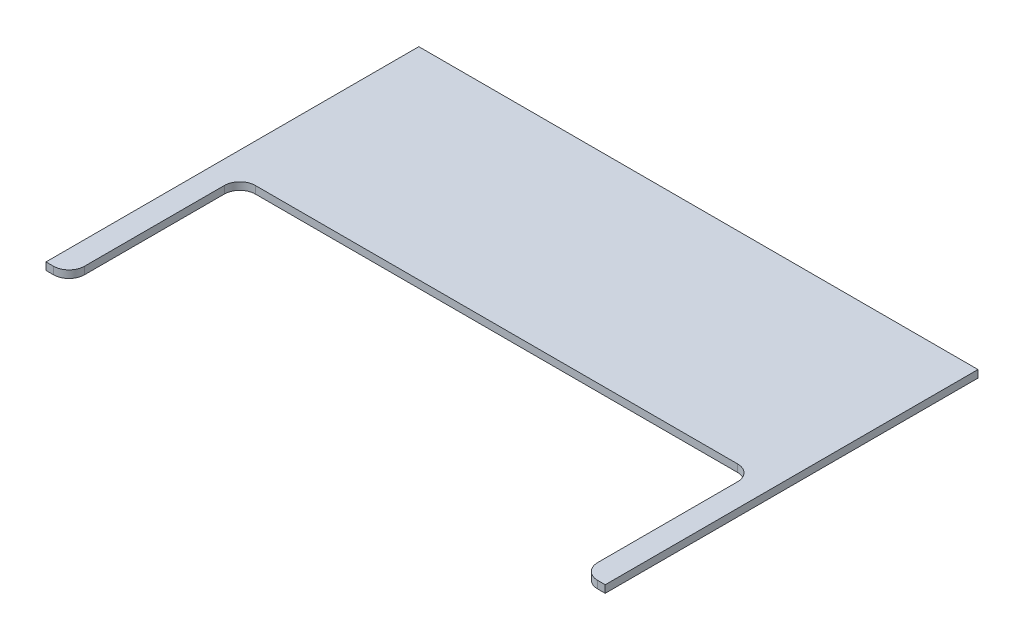
SolidWorks part; units mm, degrees
ref_plane "Front Plane" through (0, 0, 0) normal (0, 0, 1) x (1, 0, 0)
ref_plane "Top Plane" through (0, 0, 0) normal (0, 1, 0) x (1, 0, 0)
ref_plane "Right Plane" through (0, 0, 0) normal (1, 0, 0) x (0, 0, -1)
sketch "Sketch1" plane through (0, 0, 0) normal (0, 1, 0) x (1, 0, 0)
  line L0 (-547.3469, -199.6961) -> (-510.3469, -199.6961) construction
  line L1 (-547.3469, 337.9592) -> (352.6531, 337.9592)
  line L2 (-547.3469, 337.9592) -> (-547.3469, -262.0408)
  line L3 (340.6531, -262.0408) -> (352.6531, -262.0408)
  line L4 (352.6531, 337.9592) -> (352.6531, -262.0408)
  line L5 (352.6531, -199.6961) -> (315.6531, -199.6961) construction
  line L6 (0, 37.9592) -> (0, 12.9592) construction
  line L7 (-547.3469, 37.9592) -> (352.6531, 37.9592) construction
  line L8 (-510.3469, -237.0408) -> (-510.3469, -12.0408)
  line L9 (-485.3469, 12.9592) -> (290.6531, 12.9592)
  line L10 (315.6531, -12.0408) -> (315.6531, -237.0408)
  line L11 (-547.3469, -262.0408) -> (-535.3469, -262.0408)
  arc A0 (340.6531, -262.0408) -> (315.6531, -237.0408) centre (340.6531, -237.0408) cw
  arc A1 (290.6531, 12.9592) -> (315.6531, -12.0408) centre (290.6531, -12.0408) cw
  arc A2 (-510.3469, -237.0408) -> (-535.3469, -262.0408) centre (-535.3469, -237.0408) cw
  arc A3 (-510.3469, -12.0408) -> (-485.3469, 12.9592) centre (-485.3469, -12.0408) cw
  point P23 (-510.3469, -262.0408)
  dimension "D1" = 25
  dimension "D3" = 25
  dimension "D4" = 25
  dimension "D2" = 600
extrude "Boss-Extrude1" add sketch "Sketch1" along normal blind 12
